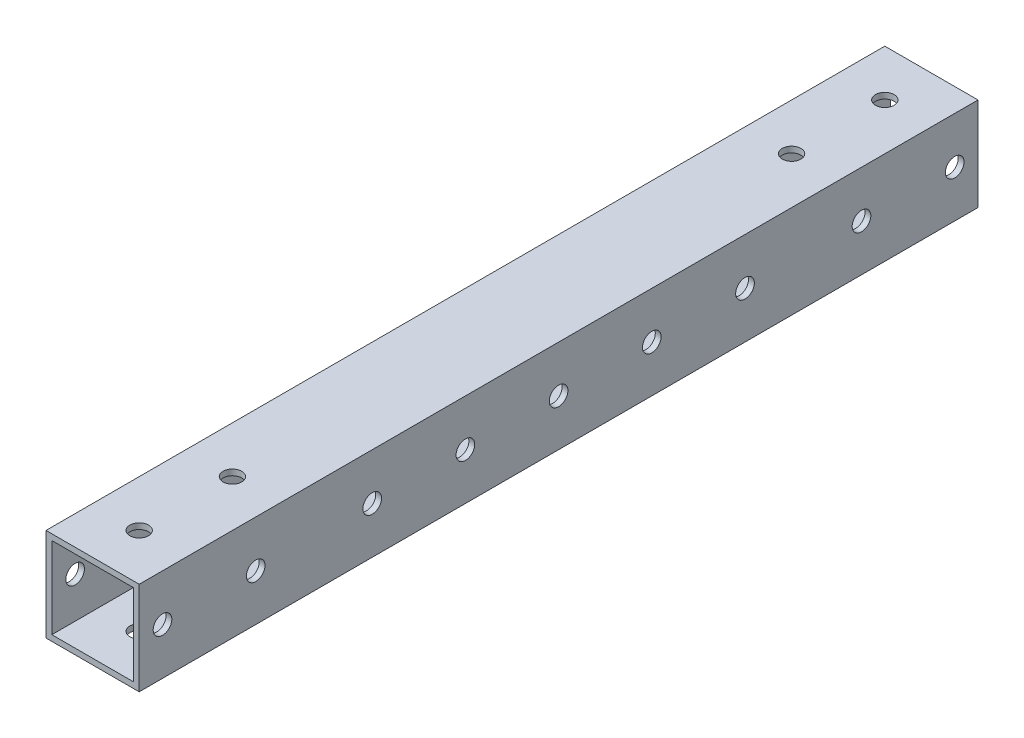
SolidWorks part; units mm, degrees
ref_plane "Front Plane" through (0, 0, 0) normal (0, 0, 1) x (1, 0, 0)
ref_plane "Top Plane" through (0, 0, 0) normal (0, 1, 0) x (1, 0, 0)
ref_plane "Right Plane" through (0, 0, 0) normal (1, 0, 0) x (0, 0, -1)
sketch "Sketch1" plane through (0, 0, 0) normal (0, 0, 1) x (1, 0, 0)
  line L1 (0, 0) -> (25.4, 0)
  line L2 (0, 0) -> (0, 25.4)
  line L3 (0, 25.4) -> (25.4, 25.4)
  line L4 (25.4, 0) -> (25.4, 25.4)
  line L5 (1.5875, 1.5875) -> (23.8125, 1.5875)
  line L6 (1.5875, 1.5875) -> (1.5875, 23.8125)
  line L7 (1.5875, 23.8125) -> (23.8125, 23.8125)
  line L8 (23.8125, 1.5875) -> (23.8125, 23.8125)
  dimension "D1" = 25.4
  dimension "D2" = 1.5875
  dimension "D3" = 1.5875
  dimension "D4" = 1.5875
  dimension "D5" = 1.5875
extrude "Boss-Extrude1" add sketch "Sketch1" along normal blind 228.6
sketch "Sketch3" plane through (0, 25.4, 0) normal (0, 1, 0) x (1, 0, 0)
  line L0 (0, -114.3) -> (25.4, -114.3) construction
  line L1 (25.4, -228.6) -> (25.4, 0) construction
  line L3 (25.4, -228.6) -> (0, -228.6) construction
  line L4 (0, -228.6) -> (0, 0) construction
  circle A4 centre (12.7, -215.9) radius 2.54
  circle A8 centre (12.7, -190.5) radius 2.54
  circle A12 centre (12.7, -12.7) radius 2.54
  circle A13 centre (12.7, -38.1) radius 2.54
  dimension "D3" = 12.7
  dimension "D1" = 5.08
  dimension "D5" = 2
  dimension "1.875" = 12.7
extrude "Cut-Extrude2" cut sketch "Sketch3" against normal through all
sketch "Sketch4" plane through (25.4, 0, 0) normal (1, 0, 0) x (0, 0, -1)
  line L0 (-114.3, 25.4) -> (-114.3, 0) construction
  line L1 (-228.6, 25.4) -> (0, 25.4) construction
  line L2 (-228.6, 0) -> (0, 0) construction
  line L3 (-228.6, 0) -> (-228.6, 25.4) construction
  circle A0 centre (-222.25, 12.7) radius 2.54
  circle A4 centre (-196.85, 12.7) radius 2.54
  circle A9 centre (-31.75, 12.7) radius 2.54
  circle A10 centre (-6.35, 12.7) radius 2.54
  circle A20 centre (-114.3, 12.7) radius 2.54
  circle A21 centre (-88.9, 12.7) radius 2.54
  circle A22 centre (-63.5, 12.7) radius 2.54
  circle A23 centre (-139.7, 12.7) radius 2.54
  circle A24 centre (-165.1, 12.7) radius 2.54
  dimension "D1" = 5.08
  dimension "D4" = 2
  dimension "D2" = 6.35
  dimension "D3" = 12.7
  dimension "D5" = 3
  dimension "D6" = 3
extrude "Cut-Extrude3" cut sketch "Sketch4" against normal through all
